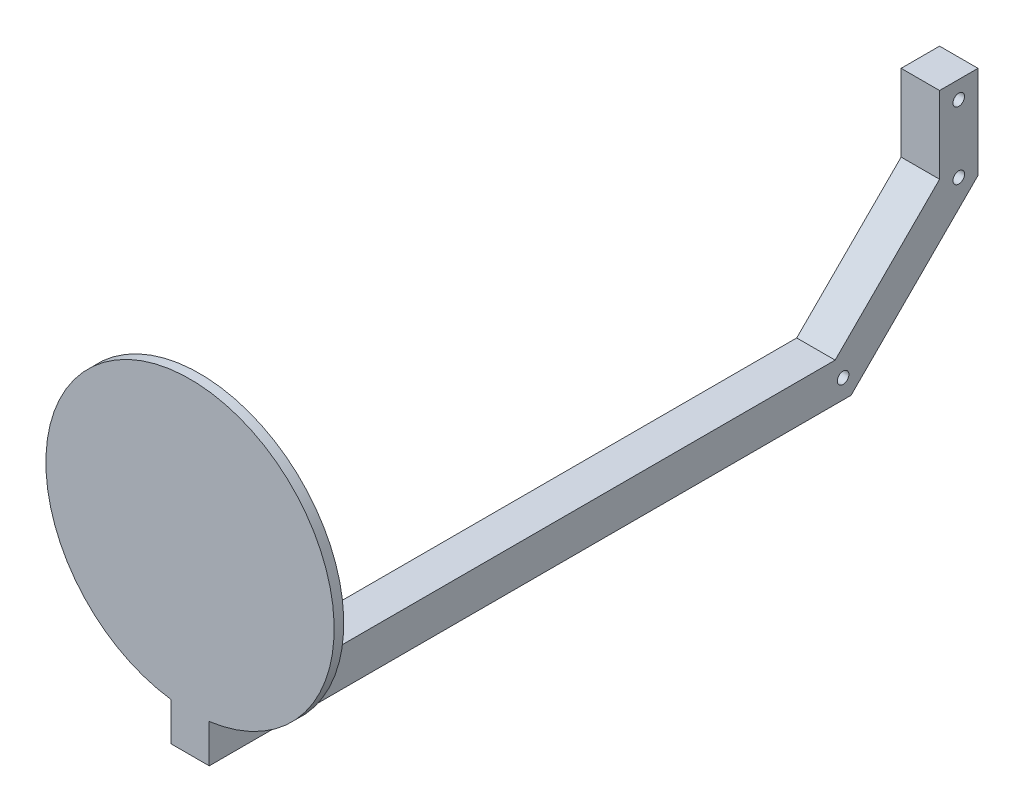
SolidWorks part; units mm, degrees
ref_plane "Plan de face" through (0, 0, 0) normal (0, 0, 1) x (1, 0, 0)
ref_plane "Plan de dessus" through (0, 0, 0) normal (0, 1, 0) x (1, 0, 0)
ref_plane "Plan de droite" through (0, 0, 0) normal (1, 0, 0) x (0, 0, -1)
sketch "Esquisse1" plane through (0, 0, 0) normal (0, 0, 1) x (1, 0, 0)
  line L0 (0, -94.3303) -> (0, 0) construction
  line L2 (-10, -74.3303) -> (-10, -94.3303)
  line L3 (-10, -94.3303) -> (10, -94.3303)
  line L4 (10, -74.3303) -> (10, -94.3303)
  arc A0 (10, -74.3303) -> (-10, -74.3303) centre (0, 0) ccw
  point P3 (0, -75)
  dimension "D1" = 150
  dimension "D2" = 20
  dimension "D3" = 20
extrude "Boss.-Extru.1" add sketch "Esquisse1" along normal blind 5
sketch "Esquisse6" plane through (10, 0, 0) normal (1, 0, 0) x (0, 0, -1)
  line L0 (-5, -94.3303) -> (-5, -74.3303) construction
  line L1 (375, -20) -> (320.6697, -74.3303)
  line L2 (-5, -94.3303) -> (-5, -74.3303)
  line L3 (328.9539, -94.3303) -> (395, -28.2843)
  line L6 (328.9539, -94.3303) -> (-5, -94.3303)
  line L7 (395, -28.2843) -> (395, 20)
  line L8 (395, 20) -> (375, 20)
  line L9 (375, 20) -> (375, -20)
  line L10 (-5, -74.3303) -> (320.6697, -74.3303)
  dimension "D1" = 20
  dimension "D2" = 20
  dimension "D3" = 135
  dimension "D4" = 20
  dimension "D5" = 20
  dimension "D6" = 400
extrude "Boss.-Extru.3" add sketch "Esquisse6" against normal up to surface (20 mm away) up to face at (-10, -84.3303, 2.5)
sketch "Esquisse7" plane through (10, 0, 0) normal (1, 0, 0) x (0, 0, -1)
  line L0 (320.6697, -74.3303) -> (328.9539, -94.3303) construction
  line L1 (375, -20) -> (395, -28.2843) construction
  line L2 (385, 10.8579) -> (385, -24.1421) construction
  line L3 (-5, -94.3303) -> (-5, -74.3303) construction
  circle A0 centre (324.8118, -84.3303) radius 3
  circle A1 centre (385, -24.1421) radius 3
  circle A2 centre (385, 10.8579) radius 3
  circle A3 centre (25, -84.3303) radius 3
  dimension "D1" = 6
  dimension "D2" = 6
  dimension "D3" = 6
  dimension "D5" = 6
  dimension "D4" = 35
  dimension "D6" = 30
extrude "Enlèv. mat.-Extru.1" cut sketch "Esquisse7" against normal up to surface (20 mm away) up to face at (-10, -46.6596, -242.1804)
